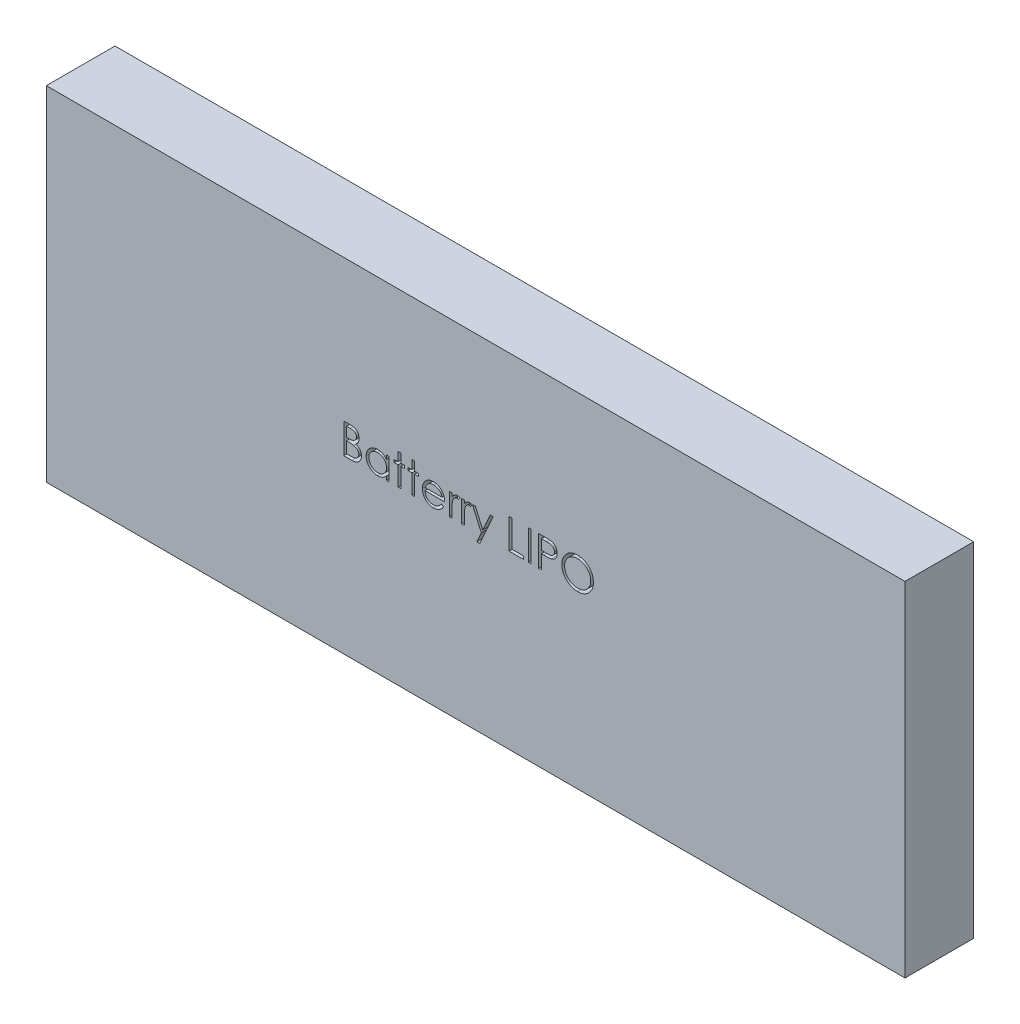
SolidWorks part; units mm, degrees
ref_plane "Alzado" through (0, 0, 0) normal (0, 0, 1) x (1, 0, 0)
ref_plane "Planta" through (0, 0, 0) normal (0, 1, 0) x (1, 0, 0)
ref_plane "Vista lateral" through (0, 0, 0) normal (1, 0, 0) x (0, 0, -1)
sketch "Croquis1" plane through (0, 0, 0) normal (0, 0, 1) x (1, 0, 0)
  line L1 (-50, -20) -> (50, -20)
  line L2 (-50, -20) -> (-50, 20)
  line L3 (-50, 20) -> (50, 20)
  line L4 (50, -20) -> (50, 20)
  line L5 (-50, -20) -> (50, 20) construction
  line L6 (-50, 20) -> (50, -20) construction
  point P0 (0, 0)
  dimension "D1" = 40
  dimension "D2" = 100
extrude "Saliente-Extruir1" add sketch "Croquis1" along normal mid plane 8
sketch "Croquis2" plane through (0, 0, 4) normal (0, 0, 1) x (1, 0, 0)
  line L0 (33.1616, 0) -> (-34.9837, 0) construction
  line L1 (0, 20) -> (0, -20) construction
  line L2 (50, 20) -> (-50, 20) construction
  line L3 (-50, -20) -> (50, -20) construction
  text T0 "Batterry LIPO"
  point P10 (9.9611, 1.9922)
  point P11 (0, -5.7772)
  point P12 (0, 0)
extrude "Cortar-Extruir1" cut sketch "Croquis2" against normal blind 25
